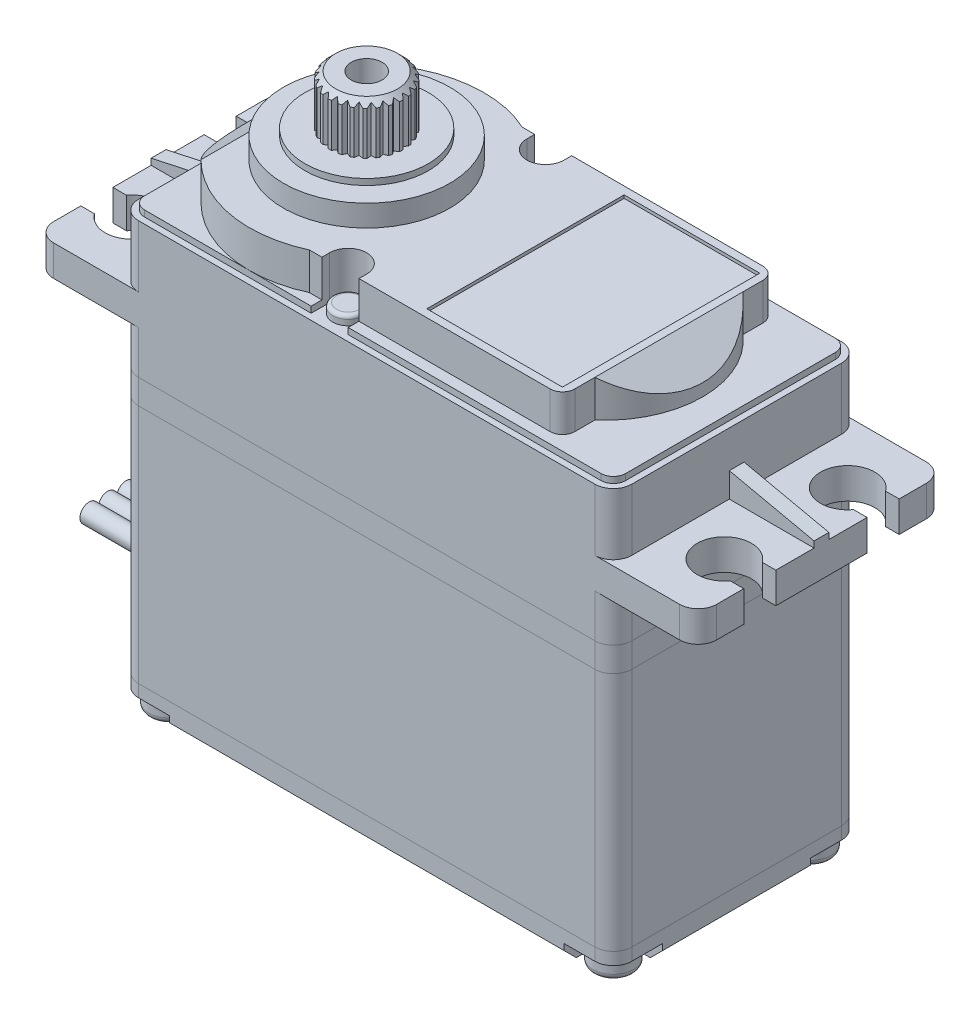
SolidWorks part; units mm, degrees
ref_plane "Front Plane" through (0, 0, 0) normal (0, 0, 1) x (1, 0, 0)
ref_plane "Top Plane" through (0, 0, 0) normal (0, 1, 0) x (1, 0, 0)
ref_plane "Right Plane" through (0, 0, 0) normal (1, 0, 0) x (0, 0, -1)
sketch "Sketch3" plane through (0, 0, 0) normal (0, 1, 0) x (1, 0, 0)
  line L1 (-20, -10) -> (20, -10)
  line L2 (-20, -10) -> (-20, 10)
  line L3 (-20, 10) -> (20, 10)
  line L4 (20, -10) -> (20, 10)
  line L5 (-20, -10) -> (20, 10) construction
  line L6 (-20, 10) -> (20, -10) construction
  point P0 (0, 0)
  dimension "D1" = 40
  dimension "D2" = 20
extrude "Boss-Extrude2" add sketch "Sketch3" against normal blind 27.5 and the other way blind 7.5
sketch "Sketch4" plane through (0, 0, 0) normal (0, 1, 0) x (1, 0, 0)
  line L0 (20, 10) -> (-20, 10) construction
  line L1 (-26.875, -10) -> (26.875, -10)
  line L2 (-26.875, -10) -> (-26.875, 10)
  line L3 (-26.875, 10) -> (26.875, 10)
  line L4 (26.875, -10) -> (26.875, 10)
  line L5 (-26.875, -10) -> (26.875, 10) construction
  line L6 (-26.875, 10) -> (26.875, -10) construction
  point P0 (0, 0)
  dimension "D1" = 53.75
extrude "Boss-Extrude3" add sketch "Sketch4" along normal blind 2.5
sketch "Sketch5" plane through (0, 2.5, 0) normal (0, 1, 0) x (1, 0, 0)
  line L1 (-24, -5) -> (24, -5) construction
  line L2 (-24, -5) -> (-24, 5) construction
  line L3 (-24, 5) -> (24, 5) construction
  line L4 (24, -5) -> (24, 5) construction
  line L5 (-24, -5) -> (24, 5) construction
  line L6 (-24, 5) -> (24, -5) construction
  circle A0 centre (-24, 5) radius 2.2
  circle A1 centre (-24, -5) radius 2.2
  circle A2 centre (24, -5) radius 2.2
  circle A3 centre (24, 5) radius 2.2
  point P0 (0, 0)
  dimension "D3" = 4.4
  dimension "D1" = 10
  dimension "D2" = 48
extrude "Cut-Extrude2" cut sketch "Sketch5" against normal through all
sketch "Sketch6" plane through (0, 2.5, 0) normal (0, 1, 0) x (1, 0, 0)
  line L0 (-24, 5) -> (-26.875, 5) construction
  line L1 (-26.875, 10) -> (-26.875, -10) construction
  line L2 (-24, 3.7) -> (-26.875, 3.7)
  line L3 (-24, 6.3) -> (-26.875, 6.3)
  line L4 (-24, -5) -> (-26.875, -5) construction
  line L5 (-24, -6.3) -> (-26.875, -6.3)
  line L6 (-24, -3.7) -> (-26.875, -3.7)
  line L7 (24, -5) -> (26.875, -5) construction
  line L8 (26.875, -10) -> (26.875, 10) construction
  line L9 (24, -3.7) -> (26.875, -3.7)
  line L10 (24, -6.3) -> (26.875, -6.3)
  line L11 (24, 5) -> (26.875, 5) construction
  line L12 (24, 6.3) -> (26.875, 6.3)
  line L13 (24, 3.7) -> (26.875, 3.7)
  arc A0 (-24, 3.7) -> (-24, 6.3) centre (-24, 5) ccw
  arc A1 (-26.875, 6.3) -> (-26.875, 3.7) centre (-26.875, 5) ccw
  arc A2 (-24, -6.3) -> (-24, -3.7) centre (-24, -5) ccw
  arc A3 (-26.875, -3.7) -> (-26.875, -6.3) centre (-26.875, -5) ccw
  arc A4 (24, -3.7) -> (24, -6.3) centre (24, -5) ccw
  arc A5 (26.875, -6.3) -> (26.875, -3.7) centre (26.875, -5) ccw
  arc A6 (24, 6.3) -> (24, 3.7) centre (24, 5) ccw
  arc A7 (26.875, 3.7) -> (26.875, 6.3) centre (26.875, 5) ccw
  point P5 (-25.4375, 5)
  point P10 (-25.4375, -5)
  point P18 (25.4375, -5)
  point P28 (25.4375, 5)
  dimension "D1" = 2.6
extrude "Cut-Extrude3" cut sketch "Sketch6" against normal through all
fillet "Fillet1" radius 1.5 4 edges at (26.875, 1.25, -10) (26.875, 1.25, 10) (-26.875, 1.25, 10) (-26.875, 1.25, -10)
fillet "Fillet2" radius 1.5 8 edges at (20, -13.75, -10) (20, 5, -10) (20, -13.75, 10) (20, 5, 10) (-20, 5, -10) (-20, -13.75, -10) (-20, 5, 10) (-20, -13.75, 10)
sketch "Sketch7" plane through (0, 7.5, 0) normal (0, 1, 0) x (1, 0, 0)
  line L8 (19.5, -8.5) -> (19.5, 8.5)
  line L9 (18.5, 9.5) -> (-18.5, 9.5)
  line L10 (-19.5, 8.5) -> (-19.5, -8.5)
  line L11 (-18.5, -9.5) -> (18.5, -9.5)
  line L12 (19.5, -8.5) -> (19.5, 8.5)
  line L13 (18.5, 9.5) -> (-18.5, 9.5)
  line L14 (-19.5, 8.5) -> (-19.5, -8.5)
  line L15 (-18.5, -9.5) -> (18.5, -9.5)
  arc A8 (19.5, 8.5) -> (18.5, 9.5) centre (18.5, 8.5) ccw
  arc A9 (-18.5, 9.5) -> (-19.5, 8.5) centre (-18.5, 8.5) ccw
  arc A10 (-19.5, -8.5) -> (-18.5, -9.5) centre (-18.5, -8.5) ccw
  arc A11 (18.5, -9.5) -> (19.5, -8.5) centre (18.5, -8.5) ccw
  arc A12 (19.5, 8.5) -> (18.5, 9.5) centre (18.5, 8.5) ccw
  arc A13 (-18.5, 9.5) -> (-19.5, 8.5) centre (-18.5, 8.5) ccw
  arc A14 (-19.5, -8.5) -> (-18.5, -9.5) centre (-18.5, -8.5) ccw
  arc A15 (18.5, -9.5) -> (19.5, -8.5) centre (18.5, -8.5) ccw
  dimension "D1" = 0.5
extrude "Boss-Extrude4" add sketch "Sketch7" along normal blind 0.5
sketch "Sketch8" plane through (0, 0, 0) normal (0, 0, 1) x (1, 0, 0)
  line L0 (20, 4.5) -> (26.875, 3)
  line L1 (20, 7.5) -> (20, 2.5) construction
  line L2 (26.875, 3) -> (26.875, 2.5)
  line L3 (26.875, 2.5) -> (20, 2.5)
  line L4 (20, 2.5) -> (20, 4.5)
  line L5 (18.5, 0) -> (25.375, 0) construction
  line L6 (-26.875, 2.5) -> (-26.875, 3)
  line L7 (-26.875, 3) -> (-20, 4.5)
  line L8 (-20, 2.5) -> (-20, 7.5) construction
  line L9 (-20, 4.5) -> (-20, 2.5)
  line L10 (-20, 2.5) -> (-26.875, 2.5)
  dimension "D1" = 0.5
  dimension "D2" = 4.5
extrude "Boss-Extrude5" add sketch "Sketch8" along normal mid plane 1.2
sketch "Sketch9" plane through (0, 8, 0) normal (0, 1, 0) x (1, 0, 0)
  line L0 (-19.5, 8.5) -> (-19.5, -8.5) construction
  line L1 (18.5, 9.5) -> (-18.5, 9.5) construction
  line L2 (-18.5, -9.5) -> (18.5, -9.5) construction
  line L3 (-6.0176, 8.625) -> (14.5, 8.625)
  line L4 (14.5, 8.625) -> (14.5, 6)
  line L5 (-6.0176, -8.625) -> (14.5, -8.625)
  line L6 (14.5, -8.625) -> (14.5, -6)
  line L7 (-19.5, 0) -> (17.25, 0) construction
  line L8 (20, -8.5) -> (20, 8.5) construction
  arc A0 (-6.0176, 8.625) -> (-6.0176, -8.625) centre (-10, 0) ccw
  arc A1 (14.5, 6) -> (14.5, -6) centre (9.3295, 0) cw
  dimension "D1" = 17.25
  dimension "D2" = 12
  dimension "D3" = 36.75
  dimension "D4" = 5.5
extrude "Boss-Extrude6" add sketch "Sketch9" along normal blind 3
sketch "Sketch10" plane through (0, 11, 0) normal (0, 1, 0) x (1, 0, 0)
  circle A0 centre (-10, 0) radius 6.75
  dimension "D1" = 13.5
extrude "Boss-Extrude7" add sketch "Sketch10" along normal blind 1.75
sketch "Sketch11" plane through (0, 0, 0) normal (0, 0, 1) x (1, 0, 0)
  line L0 (14.5, 11) -> (17.25, 9)
  line L1 (17.25, 8) -> (17.25, 11) construction
  line L2 (17.25, 9) -> (17.25, 11)
  line L3 (17.25, 11) -> (14.5, 11) construction
  line L4 (17.25, 11) -> (14.5, 11)
  line L5 (-10, 8) -> (18.5, 8) construction
  line L6 (-16.75, 11) -> (-19.5, 9)
  line L7 (-19.5, 9) -> (-19.5, 11)
  line L8 (-19.5, 11) -> (-16.75, 11)
  line L9 (-18.5, 8) -> (-10, 8) construction
  dimension "D1" = 1
  dimension "D2" = 1
extrude "Cut-Extrude4" cut sketch "Sketch11" against normal through all both and the other way through all
fillet "Fillet3" radius 1 2 edges at (14.5, 9.5, -8.625) (14.5, 9.5, 8.625)
sketch "Sketch12" plane through (0, 12.75, 0) normal (0, 1, 0) x (1, 0, 0)
  circle A0 centre (-10, 0) radius 5
  dimension "D1" = 10
extrude "Boss-Extrude8" add sketch "Sketch12" along normal blind 0.5
ref_plane "Plane2" through (0, -3.5, 0) normal (0, 1, 0) x (1, 0, 0)
split "Split1" trim tools "Plane2" bodies to split 115 resulting bodies 116 117
ref_plane "Plane3" through (0, -5.5, 0) normal (0, 1, 0) x (1, 0, 0)
split "Split2" trim tools "Plane3" bodies to split 117 resulting bodies 118 119
ref_plane "Plane4" through (0, -25, 0) normal (0, -1, 0) x (-1, 0, 0)
split "Split3" trim tools "Plane4" bodies to split 119 resulting bodies 120 121
sketch "Sketch13" plane through (0, 11, 0) normal (0, 1, 0) x (1, 0, 0)
  line L0 (-3.5, 8) -> (-3.5, -8) construction
  line L1 (-3.5, 0) -> (-10, 0) construction
  line L2 (14.5, -7.625) -> (14.5, -6) construction
  line L3 (-3.5, -8) -> (-3.5, -9.5) construction
  line L5 (-2, -8) -> (-2, -9.5)
  line L6 (-5, -8) -> (-5, -9.5)
  line L7 (-3.5, 8) -> (-3.5, 9.5) construction
  line L9 (-5, 8) -> (-5, 9.5)
  line L10 (-2, 8) -> (-2, 9.5)
  line L11 (18.5, 9.5) -> (-18.5, 9.5) construction
  circle A0 centre (-3.5, 8) radius 1.5 construction
  circle A1 centre (-3.5, -8) radius 1.5 construction
  arc A2 (-2, -8) -> (-5, -8) centre (-3.5, -8) ccw
  arc A3 (-5, -9.5) -> (-2, -9.5) centre (-3.5, -9.5) ccw
  arc A4 (-5, 8) -> (-2, 8) centre (-3.5, 8) ccw
  arc A5 (-2, 9.5) -> (-5, 9.5) centre (-3.5, 9.5) ccw
  point P12 (-3.5, -8.75)
  point P17 (-3.5, 8.75)
  dimension "D2" = 3
  dimension "D1" = 16
  dimension "D3" = 18
extrude "Cut-Extrude5" cut sketch "Sketch13" against normal up to surface (3.5 mm away)
sketch "Sketch15" plane through (0, -27.5, 0) normal (0, -1, 0) x (1, 0, 0)
  line L0 (-20, -8.5) -> (-20, 8.5) construction
  line L1 (-20, 6) -> (-18, 6)
  line L2 (-20, 6) -> (-20, 10)
  line L3 (-20, 10) -> (-16, 10)
  line L4 (-16, 8) -> (-16, 10)
  line L5 (-18.5, 10) -> (18.5, 10) construction
  line L6 (18.5, -10) -> (-18.5, -10) construction
  line L7 (-20, -6) -> (-18, -6)
  line L8 (-20, -6) -> (-20, -10)
  line L9 (-20, -10) -> (-16, -10)
  line L10 (-16, -8) -> (-16, -10)
  line L11 (20, -8.5) -> (20, 8.5) construction
  line L12 (16, -10) -> (20, -10)
  line L13 (16, -10) -> (16, -8)
  line L14 (18, -6) -> (20, -6)
  line L15 (20, -10) -> (20, -6)
  line L17 (20, 6) -> (18, 6)
  line L18 (20, 6) -> (20, 10)
  line L19 (20, 10) -> (16, 10)
  line L20 (16, 8) -> (16, 10)
  arc A0 (18, 6) -> (16, 8) centre (18, 8) cw
  arc A1 (16, -8) -> (18, -6) centre (18, -8) cw
  arc A2 (-18, -6) -> (-16, -8) centre (-18, -8) cw
  arc A3 (-18, 6) -> (-16, 8) centre (-18, 8) ccw
  dimension "D3" = 2
  dimension "D1" = 4
  dimension "D2" = 4
extrude "Cut-Extrude6" cut sketch "Sketch15" against normal blind 1.5
chamfer "Chamfer3" distance 1 angle 45 4 edges at (-20, -27.5, 0) (0, -27.5, -10) (20, -27.5, 0) (0, -27.5, 10)
sketch "Sketch16" plane through (-20, 0, 0) normal (-1, 0, 0) x (0, 0, 1)
  line L0 (0, -21.5) -> (0, 0) construction
  line L1 (-3.5, -21.5) -> (3.5, -21.5)
  line L2 (-3.5, -21.5) -> (-3.5, -25.5)
  line L3 (-3.5, -25.5) -> (3.5, -25.5)
  line L4 (3.5, -21.5) -> (3.5, -25.5)
  line L5 (6, -27.5) -> (-6, -27.5) construction
  dimension "D1" = 4
  dimension "D2" = 2
  dimension "D3" = 7
extrude "Boss-Extrude9" add sketch "Sketch16" along normal blind 1 separate body
sketch "Sketch17" plane through (-21, 0, 0) normal (-1, 0, 0) x (0, 0, 1)
  line L8 (-3.25, -21.75) -> (-3.25, -25.25)
  line L9 (-3.25, -25.25) -> (3.25, -25.25)
  line L10 (3.25, -25.25) -> (3.25, -21.75)
  line L11 (3.25, -21.75) -> (-3.25, -21.75)
  line L12 (-3.25, -21.75) -> (-3.25, -25.25)
  line L13 (-3.25, -25.25) -> (3.25, -25.25)
  line L14 (3.25, -25.25) -> (3.25, -21.75)
  line L15 (3.25, -21.75) -> (-3.25, -21.75)
  dimension "D1" = 0.25
ref_plane "Plane5" through (-26, 0, 0) normal (-1, 0, 0) x (0, 0, 1)
sketch "Sketch18" plane through (-26, 0, 0) normal (-1, 0, 0) x (0, 0, 1)
  line L0 (-3.5, -25.5) -> (3.5, -21.5) construction
  line L2 (-2.5, -24.75) -> (2.5, -24.75)
  line L3 (-2.5, -24.75) -> (-2.5, -22.25)
  line L4 (-2.5, -22.25) -> (2.5, -22.25)
  line L5 (2.5, -24.75) -> (2.5, -22.25)
  line L6 (-2.5, -24.75) -> (2.5, -22.25) construction
  line L7 (-2.5, -22.25) -> (2.5, -24.75) construction
  point P4 (0, -23.5)
  dimension "D1" = 5
  dimension "D2" = 2.5
loft "Loft1" add profiles "Sketch17", "Sketch18"
sketch "Sketch19" plane through (-26, 0, 0) normal (-1, 0, 0) x (0, 0, 1)
  line L0 (0, -24.75) -> (0, -23.5) construction
  line L1 (-2.5, -24.75) -> (2.5, -24.75) construction
  line L2 (0, -23.5) -> (0, -22.25) construction
  line L3 (2.5, -22.25) -> (-2.5, -22.25) construction
  circle A0 centre (0, -23.5) radius 0.75
  circle A1 centre (1.5, -23.5) radius 0.75
  circle A2 centre (-1.5, -23.5) radius 0.75
  dimension "D1" = 1.5
extrude "Boss-Extrude11" add sketch "Sketch19" along normal blind 5 separate body contours A2 | A0 | A1
sketch "Sketch20" plane through (0, 11, 0) normal (0, 1, 0) x (1, 0, 0)
  line L0 (-10, 0) -> (2.875, 0) construction
  line L1 (2.875, -8) -> (13.875, -8)
  line L2 (2.875, -8) -> (2.875, 8)
  line L3 (2.875, 8) -> (13.875, 8)
  line L4 (13.875, -8) -> (13.875, 8)
  line L5 (2.875, -8) -> (13.875, 8) construction
  line L6 (2.875, 8) -> (13.875, -8) construction
  line L7 (8.375, 8) -> (8.375, 8.625) construction
  line L8 (13.5, 8.625) -> (-2, 8.625) construction
  line L9 (13.875, 6.9566) -> (14.5, 6.9566) construction
  line L10 (14.5, 6) -> (14.5, 7.625) construction
  point P0 (8.375, 0)
  dimension "D1" = 16
  dimension "D2" = 11
extrude "Cut-Extrude7" cut sketch "Sketch20" against normal blind 0.25
sketch "Sketch21" plane through (0, 13.25, 0) normal (0, 1, 0) x (1, 0, 0)
  circle A0 centre (-10, 0) radius 3
  dimension "D1" = 6
extrude "Boss-Extrude12" add sketch "Sketch21" along normal blind 4 separate body
chamfer "Chamfer4" distance 0.5 angle 45 1 edges at (-10, 17.25, 3)
sketch "Sketch22" plane through (0, 17.25, 0) normal (0, 1, 0) x (1, 0, 0)
  line L0 (-10.25, 2.9896) -> (-10, 2.75)
  line L1 (-10, 2.75) -> (-9.75, 2.9896)
  line L2 (-10, 0) -> (-10, 2.75) construction
  line L3 (-10, 2.75) -> (-10, 3) construction
  arc A1 (-9.75, 2.9896) -> (-10.25, 2.9896) centre (-10, 0) ccw
  circle A2 centre (-10, 0) radius 3 construction
  dimension "D1" = 0.25
  dimension "D2" = 0.5
extrude "Cut-Extrude8" cut sketch "Sketch22" against normal up to surface (4 mm away) up to face at (-10, 13.25, 5)
pattern_circular "CirPattern1" count 25 over 360 about axis through (-10, 0, 0) along (0, 1, 0) of "Cut-Extrude8"
hole_wizard "M3x0.5 Tapped Hole1" positions "Sketch23" profile "Sketch25" tap size "M3x0.5" standard "ANSI Metric"
sketch "Sketch23" plane through (0, 17.25, 0) normal (0, 1, 0) x (1, 0, 0)
  point P0 (-10, 0)
sketch "Sketch25" plane through (-10, 17.25, 0) normal (1, 0, 0) x (0, 0, 1)
  line L0 (0, 0) -> (0, 9.2511)
  line L1 (0, 9.2511) -> (1.25, 8.5)
  line L2 (1.25, 8.5) -> (1.25, 0)
  line L5 (1.25, 0) -> (0, 0)
  line L10 (0, 9.2511) -> (-1.25, 8.5) construction
  line L11 (0, -6.35) -> (0, 107.95) construction
  dimension "Tap Drill Dia." = 2.5
  dimension "Tap Drill Depth" = 8.5
  dimension "Drill Angle" = 118
ref_plane "Plane6" through (0, -21, 0) normal (0, -1, 0) x (-1, 0, 0)
sketch "Sketch26" plane through (0, -26, 0) normal (0, -1, 0) x (1, 0, 0)
  line L0 (18, -8) -> (18, -10) construction
  line L1 (16, -10) -> (18.5, -10) construction
  line L2 (18, -8) -> (20, -8) construction
  line L3 (20, -8.5) -> (20, -6) construction
  line L5 (-18, 8) -> (18, 8) construction
  line L6 (-18, 8) -> (-18, -8) construction
  line L7 (-18, -8) -> (18, -8) construction
  line L8 (18, 8) -> (18, -8) construction
  line L9 (-18, 8) -> (18, -8) construction
  line L10 (-18, -8) -> (18, 8) construction
  circle A0 centre (18, -8) radius 1.65
  arc A1 (18, -6) -> (16, -8) centre (18, -8) ccw construction
  circle A2 centre (-18, -8) radius 1.65
  circle A3 centre (-18, 8) radius 1.65
  circle A4 centre (18, 8) radius 1.65
  point P8 (0, 0)
  dimension "D1" = 3.3
extrude "Boss-Extrude13" add sketch "Sketch26" along normal up to surface (1.5 mm away) up to face at (0, -27.5, 0)
fillet "Fillet4" radius 0.5 4 edges at (-18, -27.5, -9.65) (-18, -27.5, 6.35) (18, -27.5, 6.35) (18, -27.5, -9.65)
sketch "Sketch27" plane through (0, -21, 0) normal (0, -1, 0) x (-1, 0, 0)
  line L0 (0, 0) -> (-50000, 0) construction
  line L2 (-16, -9) -> (16, -9) construction
  line L3 (-19, 6) -> (-19, -6) construction
  line L4 (6.5, -8.5) -> (6.5, -9) construction
  line L5 (-3.5, -7.5) -> (-3.5, -9) construction
  line L6 (20, -8.5) -> (20, 8.5) construction
  line L11 (18.5, 10) -> (-18.5, 10)
  line L12 (20, -8.5) -> (20, 8.5)
  line L13 (-18.5, -10) -> (18.5, -10)
  line L14 (-20, 8.5) -> (-20, -8.5)
  line L15 (18.5, 10) -> (-18.5, 10)
  line L16 (20, -8.5) -> (20, 8.5)
  line L17 (-18.5, -10) -> (18.5, -10)
  line L18 (-20, 8.5) -> (-20, -8.5)
  circle A0 centre (-18, 8) radius 1.15 construction
  circle A1 centre (-18, -8) radius 1.15 construction
  circle A2 centre (18, -8) radius 1.15 construction
  circle A3 centre (18, 8) radius 1.15 construction
  circle A4 centre (-18, 8) radius 1.15
  circle A5 centre (-18, -8) radius 1.15
  circle A6 centre (18, -8) radius 1.15
  circle A7 centre (18, 8) radius 1.15
  arc A8 (10, 9) -> (10, -9) centre (10, 0) cw
  arc A9 (10, -9) -> (8.4576, -8.7797) centre (10, -3.4916) cw
  arc A10 (8.4576, -8.7797) -> (4.5424, -8.7797) centre (6.5, -15.4916) ccw
  arc A11 (4.5424, -8.7797) -> (0.5862, -8.443) centre (3, -3.4916) cw
  arc A12 (0.5862, -8.443) -> (-7.5862, -8.443) centre (-3.5, -16.8249) ccw
  arc A13 (-7.5862, -8.443) -> (-10, -9) centre (-10, -3.4916) cw
  arc A14 (-10, -9) -> (-10, 9) centre (-10, 0) cw
  arc A15 (10, 9) -> (8.4576, 8.7797) centre (10, 3.4916) ccw
  arc A16 (8.4576, 8.7797) -> (4.5424, 8.7797) centre (6.5, 15.4916) cw
  arc A17 (4.5424, 8.7797) -> (0.5862, 8.443) centre (3, 3.4916) ccw
  arc A18 (0.5862, 8.443) -> (-7.5862, 8.443) centre (-3.5, 16.8249) cw
  arc A19 (-7.5862, 8.443) -> (-10, 9) centre (-10, 3.4916) ccw
  arc A24 (-18.5, 10) -> (-20, 8.5) centre (-18.5, 8.5) ccw
  arc A25 (20, 8.5) -> (18.5, 10) centre (18.5, 8.5) ccw
  arc A26 (18.5, -10) -> (20, -8.5) centre (18.5, -8.5) ccw
  arc A27 (-20, -8.5) -> (-18.5, -10) centre (-18.5, -8.5) ccw
  arc A28 (-18.5, 10) -> (-20, 8.5) centre (-18.5, 8.5) ccw
  arc A29 (20, 8.5) -> (18.5, 10) centre (18.5, 8.5) ccw
  arc A30 (18.5, -10) -> (20, -8.5) centre (18.5, -8.5) ccw
  arc A31 (-20, -8.5) -> (-18.5, -10) centre (-18.5, -8.5) ccw
  dimension "D1" = 10
  dimension "D2" = 0.5
  dimension "D3" = 1.5
  dimension "D4" = 13.5
  dimension "D5" = 23.5
  dimension "D6" = 0
extrude "Cut-Extrude9" cut sketch "Sketch27" against normal blind 13
sketch "Sketch28" plane through (0, -21, 0) normal (0, 1, 0) x (1, 0, 0)
  line L4 (18.5, 10) -> (-18.5, 10)
  line L5 (-20, 8.5) -> (-20, -8.5)
  line L6 (-18.5, -10) -> (18.5, -10)
  line L7 (20, -8.5) -> (20, 8.5)
  line L8 (18.5, 10) -> (-18.5, 10)
  line L9 (-20, 8.5) -> (-20, -8.5)
  line L10 (-18.5, -10) -> (18.5, -10)
  line L11 (20, -8.5) -> (20, 8.5)
  arc A4 (20, 8.5) -> (18.5, 10) centre (18.5, 8.5) ccw
  arc A5 (-18.5, 10) -> (-20, 8.5) centre (-18.5, 8.5) ccw
  arc A6 (-20, -8.5) -> (-18.5, -10) centre (-18.5, -8.5) ccw
  arc A7 (18.5, -10) -> (20, -8.5) centre (18.5, -8.5) ccw
  arc A8 (20, 8.5) -> (18.5, 10) centre (18.5, 8.5) ccw
  arc A9 (-18.5, 10) -> (-20, 8.5) centre (-18.5, 8.5) ccw
  arc A10 (-20, -8.5) -> (-18.5, -10) centre (-18.5, -8.5) ccw
  arc A11 (18.5, -10) -> (20, -8.5) centre (18.5, -8.5) ccw
  dimension "D1" = 0
extrude "Boss-Extrude14" add sketch "Sketch28" along normal blind 1.2 from offset 1.2
pattern_linear "LPattern1" count 5 spacing 2.4 along (0, 1, 0) of "Boss-Extrude14"
sketch "Sketch29" plane through (0, 7.5, 0) normal (0, 1, 0) x (1, 0, 0)
  circle A0 centre (-3.5, -8) radius 1.25
  circle A1 centre (-3.5, 8) radius 1.25
  dimension "D1" = 2.5
extrude "Boss-Extrude15" add sketch "Sketch29" along normal blind 0.75
fillet "Fillet5" radius 0.3 2 edges at (-3.5, 8.25, -6.75) (-3.5, 8.25, 9.25)
sketch "Sketch30" plane through (0, -8, 0) normal (0, -1, 0) x (1, 0, 0)
  line L4 (20, -8.5) -> (20, 8.5)
  line L5 (18.5, 10) -> (-18.5, 10)
  line L6 (-20, 8.5) -> (-20, -8.5)
  line L7 (-18.5, -10) -> (18.5, -10)
  line L8 (20, -8.5) -> (20, 8.5)
  line L9 (18.5, 10) -> (-18.5, 10)
  line L10 (-20, 8.5) -> (-20, -8.5)
  line L11 (-18.5, -10) -> (18.5, -10)
  arc A4 (18.5, -10) -> (20, -8.5) centre (18.5, -8.5) ccw
  arc A5 (20, 8.5) -> (18.5, 10) centre (18.5, 8.5) ccw
  arc A6 (-18.5, 10) -> (-20, 8.5) centre (-18.5, 8.5) ccw
  arc A7 (-20, -8.5) -> (-18.5, -10) centre (-18.5, -8.5) ccw
  arc A8 (18.5, -10) -> (20, -8.5) centre (18.5, -8.5) ccw
  arc A9 (20, 8.5) -> (18.5, 10) centre (18.5, 8.5) ccw
  arc A10 (-18.5, 10) -> (-20, 8.5) centre (-18.5, 8.5) ccw
  arc A11 (-20, -8.5) -> (-18.5, -10) centre (-18.5, -8.5) ccw
  dimension "D1" = 0
extrude "Boss-Extrude16" add sketch "Sketch30" along normal up to surface (13 mm away)
